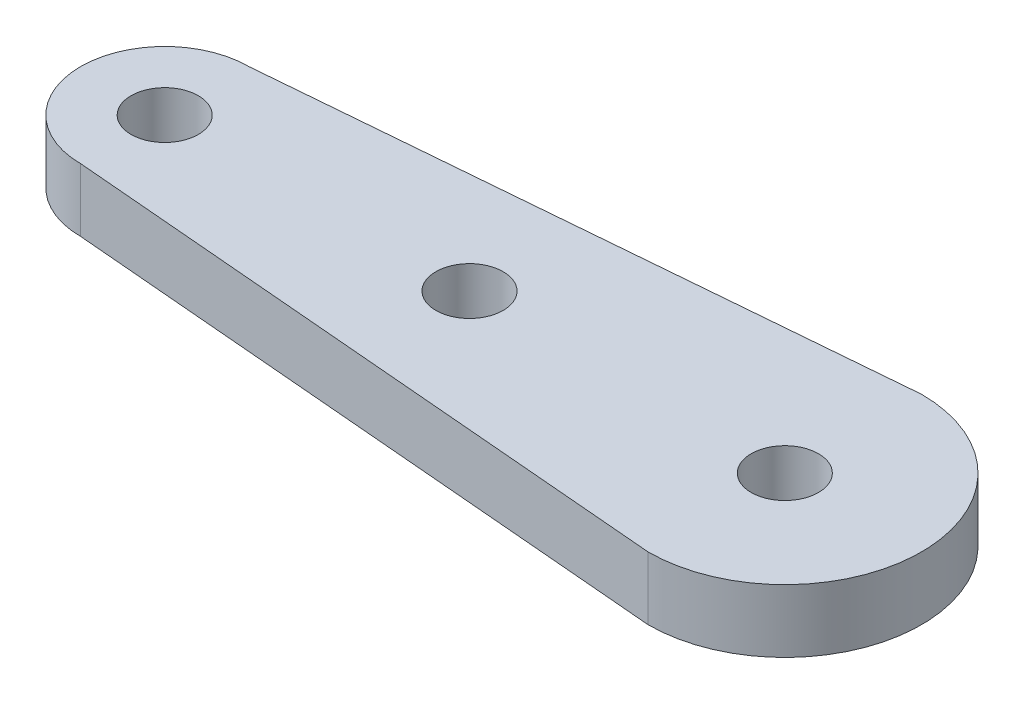
SolidWorks part; units mm, degrees
ref_plane "正面" through (0, 0, 0) normal (0, 0, 1) x (1, 0, 0)
ref_plane "平面" through (0, 0, 0) normal (0, 1, 0) x (1, 0, 0)
ref_plane "右側面" through (0, 0, 0) normal (1, 0, 0) x (0, 0, -1)
sketch "ｽｹｯﾁ1" plane through (0, 0, 0) normal (0, 1, 0) x (1, 0, 0)
  line L0 (-1.65, 0) -> (1.65, 0) construction
  line L1 (0, 6.5) -> (-29.5, 4)
  line L2 (-29.5, -4) -> (0, -6.5)
  circle A0 centre (0, 0) radius 1.6
  circle A1 centre (-15, 0) radius 1.6
  circle A2 centre (-29.5, 0) radius 1.6
  arc A3 (0, -6.5) -> (0, 6.5) centre (0, 0) ccw
  arc A4 (-29.5, 4) -> (-29.5, -4) centre (-29.5, 0) ccw
  dimension "D1" = 3.2
  dimension "D2" = 3.2
  dimension "D3" = 15
  dimension "D4" = 3.2
  dimension "D5" = 14.5
  dimension "D6" = 13
  dimension "D7" = 8
extrude "ﾎﾞｽ - 押し出し1" add sketch "ｽｹｯﾁ1" along normal blind 3
